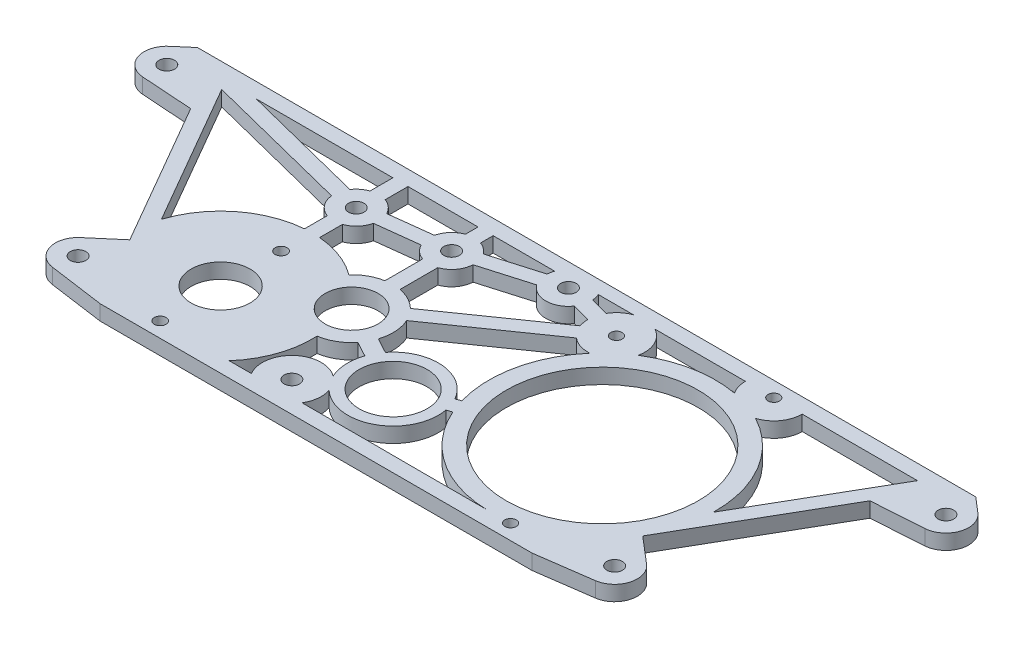
SolidWorks part; units mm, degrees
ref_plane "Front Plane" through (0, 0, 0) normal (0, 0, 1) x (1, 0, 0)
ref_plane "Top Plane" through (0, 0, 0) normal (0, 1, 0) x (1, 0, 0)
ref_plane "Right Plane" through (0, 0, 0) normal (1, 0, 0) x (0, 0, -1)
sketch "Sketch1" plane through (0, 0, 0) normal (0, 1, 0) x (1, 0, 0)
  line L0 (-155.0877, 84.2963) -> (-89.4632, -29.3687)
  line L1 (-89.4632, -29.3687) -> (150.6688, -29.3687)
  line L2 (150.6688, -29.3687) -> (216.2933, 84.2963)
  line L3 (216.2933, 84.2963) -> (-155.0877, 84.2963)
  line L4 (-5.496, 21.6549) -> (-41.275, 2.3813) construction
  line L5 (-5.496, 21.6549) -> (32.4838, 1.1113) construction
  line L6 (60.0176, 67.4068) -> (115.6073, 77.9462) construction
  line L7 (115.6073, 77.9462) -> (96.9399, 24.5341) construction
  line L8 (96.9399, 24.5341) -> (105.9556, -23.0187) construction
  line L9 (60.0176, 67.4068) -> (96.9399, 24.5341) construction
  line L10 (44.2408, 77.1526) -> (117.1825, 90.9819)
  line L11 (44.2408, 77.1526) -> (56.7891, 30.5539)
  line L12 (-140.423, 84.2963) -> (-74.7985, -29.3687) construction
  line L13 (-125.7583, 84.2963) -> (-60.1338, -29.3687) construction
  line L14 (121.3394, -29.3687) -> (186.9639, 84.2963) construction
  line L15 (136.0041, -29.3687) -> (201.6286, 84.2963) construction
  line L16 (-82.1308, -16.6687) -> (143.3365, -16.6687) construction
  circle A0 centre (-41.275, 2.3813) radius 12.3825
  circle A1 centre (-41.275, 27.7812) radius 2.4892
  circle A2 centre (-41.275, -23.0187) radius 2.4892
  circle A3 centre (-41.275, 2.3813) radius 32.2072
  circle A4 centre (-5.496, 21.6549) radius 11.1252
  circle A5 centre (32.4838, 1.1113) radius 14.3002
  circle A6 centre (-5.496, 21.6549) radius 31.75
  circle A7 centre (60.0176, 67.4068) radius 2.413
  circle A8 centre (115.6073, 77.9462) radius 2.413
  circle A9 centre (105.9556, -23.0187) radius 2.413
  circle A10 centre (32.4838, 1.1113) radius 29.4316
  circle A11 centre (96.9399, 24.5341) radius 40.3225
  circle A12 centre (-133.0907, 71.5963) radius 3.2639
  circle A13 centre (-82.1308, -16.6687) radius 3.2639
  circle A14 centre (194.2963, 71.5963) radius 3.2639
  circle A15 centre (143.3365, -16.6687) radius 3.2639
  point P24 (125.0056, -23.0187)
  dimension "D2" = 56.58
  dimension "D3" = 48.4
  dimension "D4" = 56.5803
  dimension "D5" = 6.35
  dimension "D9" = 56.5803
  dimension "D11" = 12.7
  dimension "D13" = 120
  dimension "D10" = 6.35
  dimension "D12" = 120
  dimension "D14" = 12.7
  dimension "D16" = 113.665
  dimension "D18" = 12.7
  dimension "D19" = 12.7
  dimension "D21" = 12.7
  dimension "D22" = 40.64
  dimension "D23" = 22.2504
  dimension "D24" = 4.9784
  dimension "D25" = 6.5278
  dimension "D26" = 6.5278
  dimension "D27" = 6.5278
  dimension "D28" = 6.5278
  dimension "D29" = 4.9784
  dimension "D30" = 24.765
  dimension "D31" = 28.6004
  dimension "D32" = 80.645
  dimension "D7" = 19.05
  dimension "D20" = 12.7
  dimension "D34" = 63.5
  dimension "D36" = 30.48
  dimension "D37" = 50.8
  dimension "D38" = 25.4
  dimension "D39" = 6.5278
  dimension "D6" = 25.4
  dimension "D8" = 6.35
  dimension "D15" = 25.4
  dimension "D17" = 12.7
  dimension "D33" = 68.58
  dimension "D35" = 43.18
extrude "Boss-Extrude1" add sketch "Sketch1" along normal blind 6.35
sketch "Sketch3" plane through (0, 6.35, 0) normal (0, 1, 0) x (1, 0, 0)
  line L0 (194.094, 84.2963) -> (200.483, 78.8385)
  line L1 (-155.0877, 84.2963) -> (-89.4632, -29.3687) construction
  line L2 (216.2933, 84.2963) -> (-155.0877, 84.2963) construction
  line L3 (121.3394, -29.3687) -> (186.9639, 84.2963) construction
  line L4 (194.9394, 62.093) -> (173.2994, 60.6286)
  line L5 (-88.3175, -9.4265) -> (-77.1535, 0.1103)
  line L6 (-89.4632, -29.3687) -> (150.6688, -29.3687) construction
  line L7 (138.3591, 0.1103) -> (149.5231, -9.4265)
  line L8 (-125.7583, 84.2963) -> (-60.1338, -29.3687) construction
  line L9 (121.3394, -29.3687) -> (144.6581, -26.1016)
  line L10 (-60.1338, -29.3687) -> (-83.4525, -26.1016)
  line L11 (-139.2773, 78.8385) -> (-132.8884, 84.2963)
  line L12 (150.6688, -29.3687) -> (216.2933, 84.2963) construction
  line L13 (-133.7338, 62.093) -> (-112.0938, 60.6286)
  line L14 (138.3591, 0.1103) -> (173.2994, 60.6286)
  line L15 (-77.1535, 0.1103) -> (-112.0938, 60.6286)
  line L16 (68.1814, -23.083) -> (96.0763, -23.083)
  line L17 (-112.5461, 74.1121) -> (-77.9689, 14.2225)
  line L18 (65.6244, 77.9463) -> (103.6693, 77.9463)
  line L19 (-132.8884, 84.2963) -> (179.0981, 84.2962)
  line L20 (-60.1338, -29.3687) -> (113.4736, -29.3687)
  line L21 (-101.8004, 77.9463) -> (-44.45, 77.9463)
  line L22 (-12.2664, -23.0188) -> (20.5334, -23.0188)
  line L23 (127.5453, 77.9463) -> (175.9654, 77.9463)
  line L24 (-5.496, 21.6549) -> (32.4838, 1.1113) construction
  line L25 (32.4838, 1.1113) -> (96.9399, 24.5341) construction
  line L26 (96.9399, 24.5341) -> (60.0176, 67.4068) construction
  line L27 (60.0176, 67.4068) -> (-5.496, 21.6549) construction
  line L28 (-5.496, 21.6549) -> (-5.496, 77.9463) construction
  line L29 (32.4838, 1.1113) -> (32.4838, -23.0188) construction
  line L30 (96.9399, 24.5341) -> (115.6073, 77.9462) construction
  line L31 (-41.275, 27.7812) -> (-41.275, 77.9463) construction
  line L32 (96.9399, 24.5341) -> (105.9556, -23.0187) construction
  line L33 (-44.45, 77.9463) -> (-44.45, 68.3571)
  line L34 (-38.1, 77.9463) -> (-38.1, 68.3571)
  line L35 (-8.671, 77.9463) -> (-8.671, 72.639)
  line L36 (-2.321, 77.9463) -> (-2.321, 72.639)
  line L37 (48.7647, 63.4209) -> (6.7643, 34.0896)
  line L38 (10.4001, 28.8835) -> (52.4004, 58.2147)
  line L39 (-41.275, 59.3769) -> (-5.496, 63.6588) construction
  line L40 (-114.7598, 77.9462) -> (-41.275, 59.3769) construction
  line L41 (8.0969, 10.6927) -> (14.4518, 7.2552)
  line L42 (49.0535, 10.5107) -> (51.1939, 11.2885)
  line L43 (11.118, 16.2779) -> (17.4729, 12.8405)
  line L44 (53.3627, 5.3204) -> (51.2223, 4.5425)
  line L45 (175.9654, 77.9463) -> (144.5545, 23.541)
  line L46 (194.094, 84.2963) -> (179.0981, 84.2962)
  line L47 (97.9473, 2.1759) -> (99.8881, -8.0608)
  line L48 (104.1862, 3.3588) -> (106.127, -6.8779)
  line L49 (-5.496, 63.6588) -> (32.4838, 74.7713) construction
  line L50 (32.4838, 74.7713) -> (60.0176, 67.4068) construction
  line L51 (96.9399, 24.5341) -> (151.9268, 24.5341) construction
  line L52 (113.4736, -29.3687) -> (121.3394, -29.3687)
  line L53 (-32.7356, 63.5965) -> (-14.7899, 65.7442)
  line L54 (-38.1, 77.9463) -> (-8.671, 77.9463)
  line L55 (-2.321, 77.9463) -> (23.5036, 77.9463)
  line L56 (-31.9811, 57.2915) -> (-14.0354, 59.4391)
  line L57 (20.5334, -23.0188) -> (47.8141, -23.0188)
  line L58 (-101.8004, 77.9463) -> (-49.2037, 64.6552)
  line L59 (-112.5461, 74.1121) -> (-50.7594, 58.4988)
  line L60 (2.2313, 69.2278) -> (22.9733, 75.2967)
  line L61 (4.0145, 63.1333) -> (24.7565, 69.2022)
  line L62 (40.3388, 69.3837) -> (48.08, 67.3132)
  line L63 (41.9795, 75.5181) -> (49.7207, 73.4475)
  line L64 (-44.45, 50.3966) -> (-44.45, 40.8075)
  line L65 (-38.1, 50.3966) -> (-38.1, 40.8075)
  line L66 (-8.671, 54.6785) -> (-8.671, 38.8264)
  line L67 (-2.321, 54.6785) -> (-2.321, 38.8264)
  line L68 (41.1965, 78.6203) -> (55.9219, 78.6203)
  line L69 (47.8141, -23.0188) -> (68.1814, -23.083)
  line L70 (-41.275, 2.3813) -> (-5.496, 21.6549) construction
  line L71 (-140.423, 84.2963) -> (-74.7985, -29.3687) construction
  arc A0 (-12.2664, -23.0188) -> (-2.771, 4.4064) centre (-41.275, 2.3813) ccw
  arc A1 (-139.2773, 78.8385) -> (-133.7338, 62.093) centre (-133.0907, 71.5962) ccw
  arc A2 (-88.3175, -9.4265) -> (-83.4525, -26.1016) centre (-82.1308, -16.6687) ccw
  arc A3 (144.5545, 23.541) -> (144.5649, 24.5341) centre (96.9399, 24.5341) ccw
  arc A4 (194.9394, 62.093) -> (200.483, 78.8385) centre (194.2963, 71.5963) ccw
  arc A5 (-2.771, 4.4064) -> (8.0969, 10.6927) centre (-5.496, 21.6549) ccw
  arc A6 (6.7643, 34.0896) -> (-2.321, 38.8264) centre (-5.496, 21.6549) ccw
  arc A7 (14.4518, 7.2552) -> (22.8645, -15.3317) centre (32.4838, 1.1113) ccw
  arc A8 (144.6581, -26.1016) -> (149.5231, -9.4265) centre (143.3365, -16.6687) ccw
  arc A9 (55.9219, 78.6203) -> (49.7207, 73.4475) centre (60.0176, 67.4068) ccw
  arc A10 (103.6693, 77.9463) -> (105.6537, 71.3552) centre (115.6073, 77.9462) ccw
  arc A11 (52.4004, 58.2147) -> (60.7488, 55.4912) centre (60.0176, 67.4068) ccw
  arc A12 (-18.4003, 33.42) -> (-38.1, 40.8075) centre (-41.275, 2.3813) ccw
  arc A13 (105.6537, 71.3552) -> (71.6929, 64.9165) centre (96.9399, 24.5341) ccw
  arc A14 (-8.671, 38.8264) -> (-18.4003, 33.42) centre (-5.496, 21.6549) ccw
  arc A15 (-44.45, 40.8075) -> (-77.9689, 14.2225) centre (-41.275, 2.3813) ccw
  arc A16 (11.118, 16.2779) -> (10.4001, 28.8835) centre (-5.496, 21.6549) ccw
  arc A17 (144.5545, 23.541) -> (119.2883, 66.5899) centre (96.9399, 24.5341) ccw
  arc A18 (-38.1, 50.3966) -> (-31.9811, 57.2915) centre (-41.275, 59.3769) ccw
  arc A19 (71.6929, 64.9165) -> (65.6244, 77.9463) centre (60.0176, 67.4068) ccw
  arc A20 (144.5545, 23.541) -> (119.2883, 66.5899) centre (96.9399, 24.5341) ccw
  arc A21 (60.7488, 55.4912) -> (96.0763, -23.083) centre (96.9399, 24.5341) ccw
  arc A22 (119.2883, 66.5899) -> (127.5453, 77.9463) centre (115.6073, 77.9462) ccw
  circle A23 centre (-5.496, 63.6588) radius 3.2639
  arc A24 (49.0535, 10.5107) -> (17.4729, 12.8405) centre (32.4838, 1.1113) ccw
  arc A25 (105.6537, 71.3552) -> (71.6929, 64.9165) centre (96.9399, 24.5341) ccw
  arc A26 (60.7488, 55.4912) -> (72.6804, -16.449) centre (96.9399, 24.5341) ccw
  arc A27 (-44.45, 68.3571) -> (-49.2037, 64.6552) centre (-41.275, 59.3769) ccw
  arc A28 (-50.7594, 58.4988) -> (-44.45, 50.3966) centre (-41.275, 59.3769) ccw
  arc A29 (-32.7356, 63.5965) -> (-38.1, 68.3571) centre (-41.275, 59.3769) ccw
  arc A30 (-14.0354, 59.4391) -> (-8.671, 54.6785) centre (-5.496, 63.6588) ccw
  arc A31 (23.5036, 77.9463) -> (22.9733, 75.2967) centre (32.4838, 74.7713) ccw
  circle A32 centre (-41.275, 59.3769) radius 3.2639
  circle A33 centre (7.7188, -16.6687) radius 3.2586
  arc A34 (45.372, -12.9172) -> (51.2223, 4.5425) centre (32.4838, 1.1113) ccw
  circle A35 centre (7.7188, -16.6687) radius 12.3825
  arc A36 (-8.671, 72.639) -> (-14.7899, 65.7442) centre (-5.496, 63.6588) ccw
  arc A37 (105.6537, 71.3552) -> (72.6804, -16.449) centre (96.9399, 24.5341) ccw
  circle A38 centre (32.4838, 74.7713) radius 3.2639
  arc A39 (2.2313, 69.2278) -> (-2.321, 72.639) centre (-5.496, 63.6588) ccw
  arc A40 (-2.321, 54.6785) -> (4.0145, 63.1333) centre (-5.496, 63.6588) ccw
  arc A41 (24.7565, 69.2022) -> (40.3388, 69.3837) centre (32.4838, 74.7713) ccw
  arc A42 (41.9795, 75.5181) -> (41.1965, 78.6203) centre (32.4838, 74.7713) ccw
  arc A43 (48.08, 67.3132) -> (48.7647, 63.4209) centre (60.0176, 67.4068) ccw
  arc A44 (22.8645, -15.3317) -> (45.372, -12.9172) centre (32.4838, 1.1113) ccw
  point P3 (-147.7554, 71.5962)
  point P6 (-96.7955, -16.6687)
  point P15 (159.7584, -16.6687)
  point P16 (209.4003, 72.3572)
  point P41 (-41.275, 59.3769)
  point P43 (-5.496, 58.3863)
  point P86 (204.2606, 63.455)
  point P106 (-142.6157, 62.694)
  point P148 (-41.275, -23.0187)
  dimension "D3" = 19.05
  dimension "D4" = 25.4
  dimension "D5" = 19.05
  dimension "D8" = 34.925
  dimension "D9" = 19.05
  dimension "D10" = 25.4
  dimension "D11" = 23.876
  dimension "D12" = 23.876
  dimension "D13" = 6.35
  dimension "D24" = 12.7
  dimension "D7" = 95.25
  dimension "D17" = 38.1
  dimension "D6" = 19.05
  dimension "D23" = 38.5572
  dimension "D26" = 24.765
  dimension "D27" = 19.05
  dimension "D28" = 6.5278
  dimension "D22" = 9.525
  dimension "D31" = 24.765
  dimension "D32" = 113.665
  dimension "D30" = 14.2875
  dimension "D33" = 19.05
  dimension "D34" = 19.05
  dimension "D36" = 6.5278
  dimension "D14" = 6.35
  dimension "D15" = 6.35
  dimension "D16" = 6.35
  dimension "D18" = 6.35
  dimension "D19" = 6.35
  dimension "D20" = 6.35
  dimension "D21" = 6.35
  dimension "D25" = 6.35
  dimension "D29" = 6.35
  dimension "D35" = 6.35
  dimension "D37" = 6.35
  dimension "D38" = 6.35
  dimension "D39" = 40.64
  dimension "D40" = 43.18
  dimension "D41" = 68.58
  dimension "D42" = 12.7
  dimension "D43" = 21.997
  dimension "D44" = 12.7
  dimension "D45" = 7.976
  dimension "D46" = 100.505
  dimension "D47" = 123.871
  dimension "D48" = 40.505
  dimension "D49" = 18.8588
  dimension "D50" = 23.5464
  dimension "D51" = 14.6828
  dimension "D52" = 14.6647
extrude "Cut-Extrude2" cut sketch "Sketch3" against normal through all
